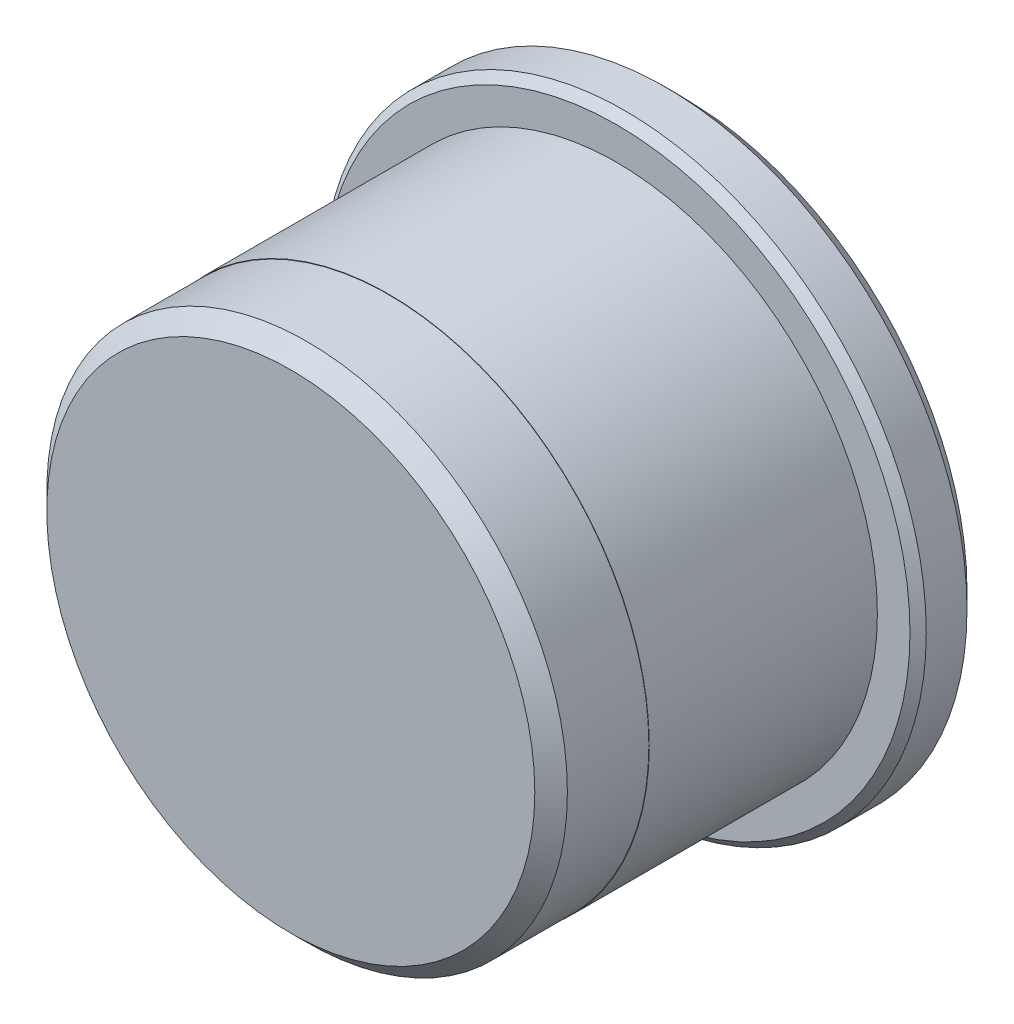
SolidWorks part; units mm, degrees
material "AISI 4140"
ref_plane "Front Plane" through (0, 0, 0) normal (0, 0, 1) x (1, 0, 0)
ref_plane "Top Plane" through (0, 0, 0) normal (0, 1, 0) x (1, 0, 0)
ref_plane "Right Plane" through (0, 0, 0) normal (1, 0, 0) x (0, 0, -1)
sketch "Sketch1" plane through (0, 0, 0) normal (1, 0, 0) x (0, 0, -1)
  line L0 (0, 0) -> (24, 0) construction
  line L1 (0, 0) -> (0, 14.975)
  line L2 (0, 14.975) -> (1, 15.975)
  line L3 (1, 15.975) -> (6, 15.975)
  line L4 (6, 15.975) -> (6, 16)
  line L5 (6, 16) -> (20, 16)
  line L6 (20, 16) -> (20, 18)
  line L7 (20, 18) -> (20.5, 18.5)
  line L8 (20.5, 18.5) -> (23, 18.5)
  line L9 (23, 18.5) -> (24, 17.5)
  line L10 (24, 17.5) -> (24, 14.0774)
  line L11 (24, 14.0774) -> (23, 13.5)
  line L12 (23, 13.5) -> (9, 13.5)
  line L13 (7, 13.75) -> (7, 11)
  line L14 (7, 11) -> (5, 11)
  line L15 (5, 11) -> (5, 1.5)
  line L16 (5, 1.5) -> (4.0987, 0)
  line L17 (4.0987, 0) -> (0, 0)
  line L18 (9, 13.5) -> (9, 13.75)
  line L19 (9, 13.75) -> (7, 13.75)
  dimension "D1" = 24
  dimension "D2" = 45
  dimension "D3" = 1
  dimension "D4" = 59
  dimension "D5" = 1.5
  dimension "D6" = 45
  dimension "D7" = 0.5
  dimension "D8" = 45
  dimension "D9" = 1
  dimension "D10" = 30
  dimension "D11" = 1
  dimension "D12" = 16
  dimension "D13" = 15.975
  dimension "D14" = 18.5
  dimension "D15" = 13.5
  dimension "D16" = 11
  dimension "D17" = 17
  dimension "D18" = 19
  dimension "D19" = 6
  dimension "D21" = 2
  dimension "D22" = 13.75
  dimension "D23" = 4
revolve "Revolve2" add sketch "Sketch1" angle 360 about L0
sketch "Sketch2" plane through (0, 0, 0) normal (0, 1, 0) x (0, 0, -1)
  line L1 (24, -17.5) -> (24, 17.5) construction
  circle A1 centre (27.3, 0) radius 4
  dimension "D2" = 0.7
  dimension "D1" = 8
extrude "Cut-Extrude3" cut sketch "Sketch2" along normal through all contours A1
pattern_circular "CirPattern1" count 3 over 360 about axis through (0, 0, -4.0987) along (0, 0, -1) of "Cut-Extrude3"
